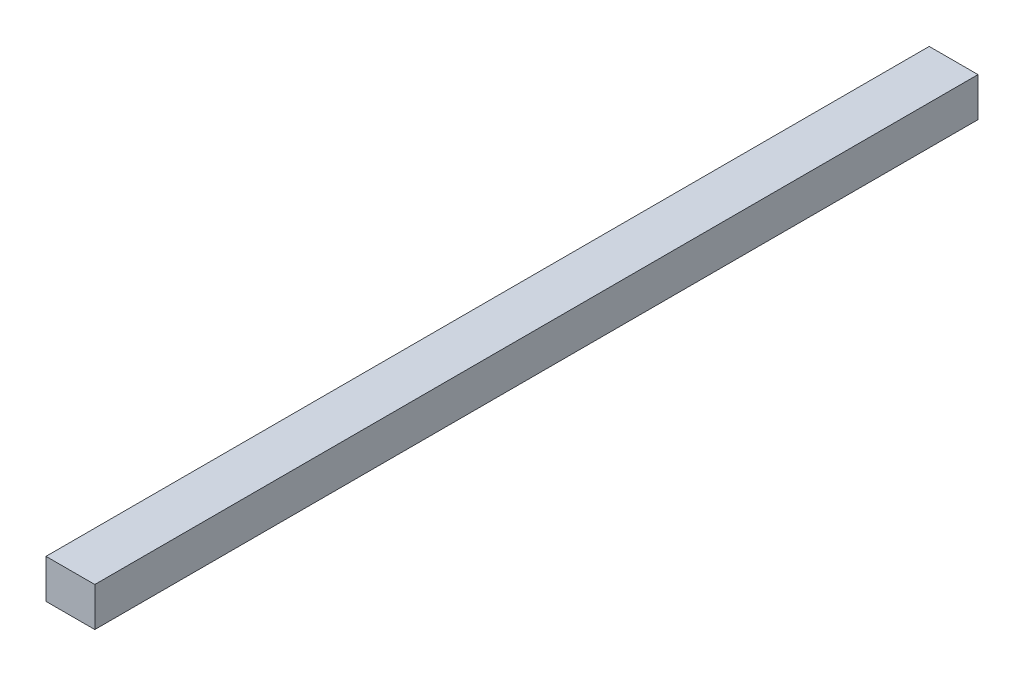
SolidWorks part; units mm, degrees
ref_plane "Plan de face" through (0, 0, 0) normal (0, 0, 1) x (1, 0, 0)
ref_plane "Plan de dessus" through (0, 0, 0) normal (0, 1, 0) x (1, 0, 0)
ref_plane "Plan de droite" through (0, 0, 0) normal (1, 0, 0) x (0, 0, -1)
sketch "Esquisse1" plane through (0, 0, 0) normal (0, 0, 1) x (1, 0, 0)
  line L1 (0, 0) -> (50, 0)
  line L2 (0, 0) -> (0, 40)
  line L3 (0, 40) -> (50, 40)
  line L4 (50, 0) -> (50, 40)
  dimension "D1" = 50
  dimension "D2" = 40
extrude "Boss.-Extru.1" add sketch "Esquisse1" along normal blind 905
